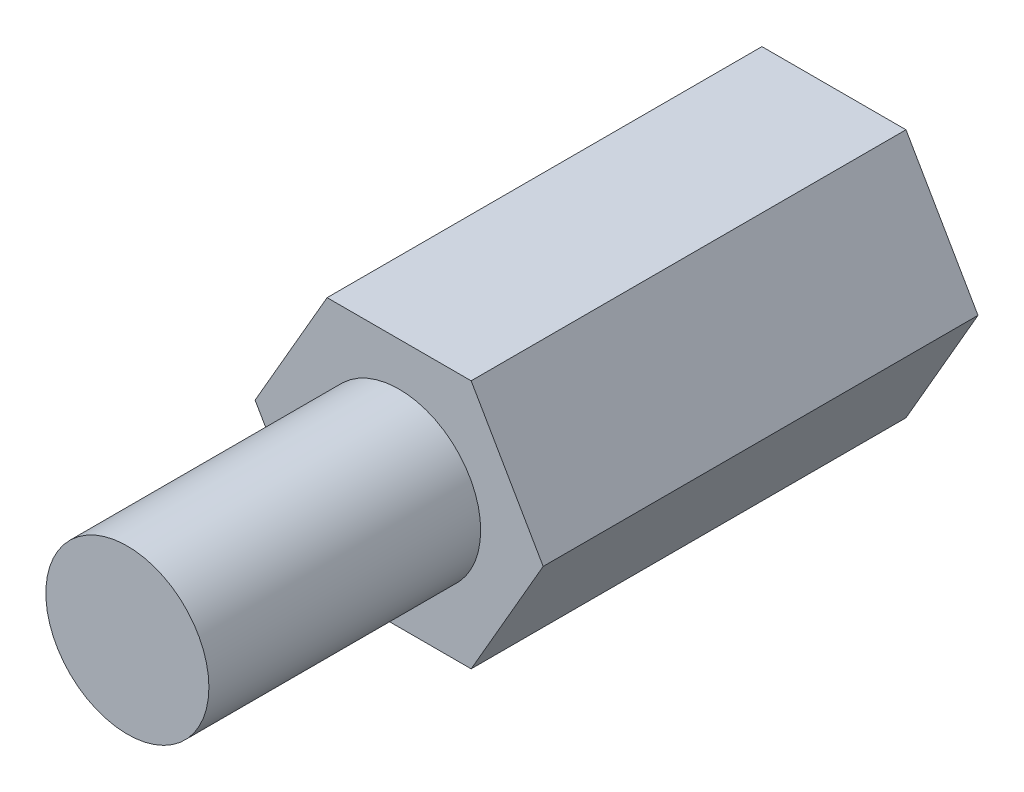
SolidWorks part; units mm, degrees
material "黃銅"
ref_plane "前基準面" through (0, 0, 0) normal (0, 0, 1) x (1, 0, 0)
ref_plane "上基準面" through (0, 0, 0) normal (0, 1, 0) x (1, 0, 0)
ref_plane "右基準面" through (0, 0, 0) normal (1, 0, 0) x (0, 0, -1)
sketch "草圖1" plane through (0, 0, 0) normal (0, 0, 1) x (1, 0, 0)
  line L1 (1.325, 2.295) -> (-1.325, 2.295)
  line L2 (-1.325, 2.295) -> (-2.65, 0)
  line L3 (-2.65, 0) -> (-1.325, -2.295)
  line L4 (-1.325, -2.295) -> (1.325, -2.295)
  line L5 (1.325, -2.295) -> (2.65, 0)
  line L6 (2.65, 0) -> (1.325, 2.295)
  circle A0 centre (0, 0) radius 2.295 construction
  dimension "D1" = 5.3
extrude "填料-伸長1" add sketch "草圖1" along normal blind 8
sketch "草圖2" plane through (0, 0, 0) normal (0, 0, -1) x (-1, 0, 0)
  circle A0 centre (0, 0) radius 1.25
  dimension "D1" = 2.5
extrude "除料-伸長1" cut sketch "草圖2" against normal blind 3
sketch "草圖3" plane through (0, 0, 8) normal (0, 0, 1) x (1, 0, 0)
  circle A0 centre (0, 0) radius 1.5
  dimension "D1" = 3
extrude "填料-伸長2" add sketch "草圖3" along normal blind 5
